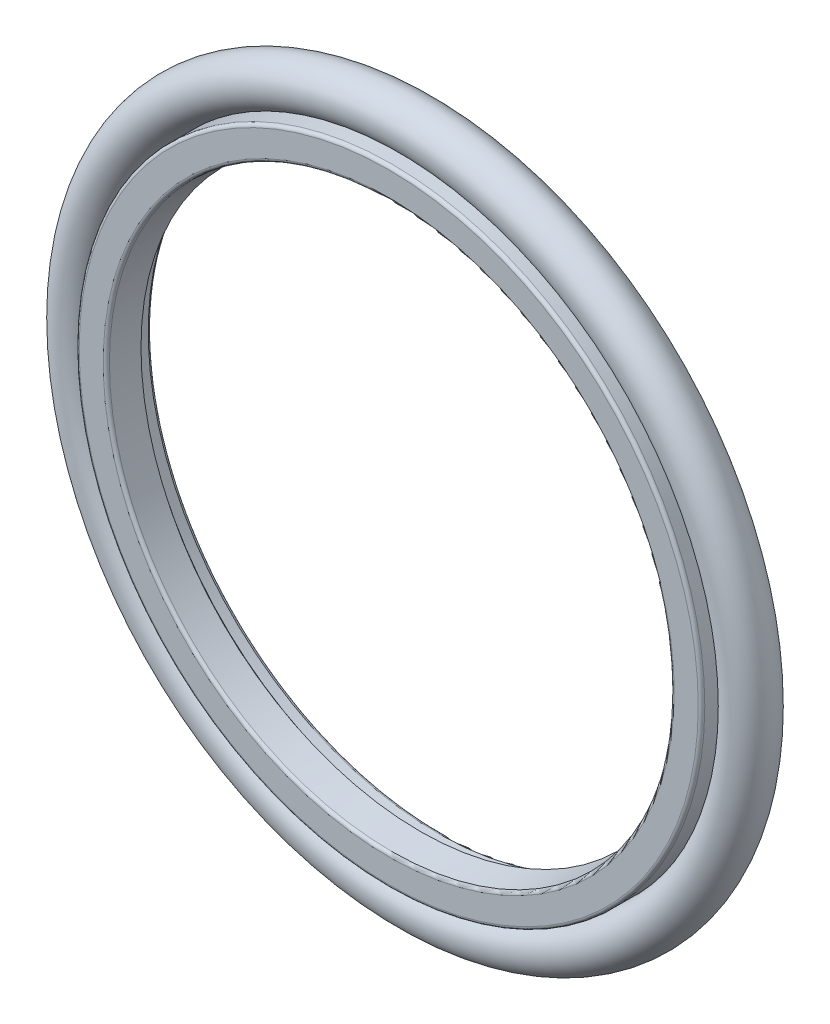
SolidWorks part; units mm, degrees
material "PTFE+NBR"
ref_plane "Front Plane" through (0, 0, 0) normal (0, 0, 1) x (1, 0, 0)
ref_plane "Top Plane" through (0, 0, 0) normal (0, 1, 0) x (1, 0, 0)
ref_plane "Right Plane" through (0, 0, 0) normal (1, 0, 0) x (0, 0, -1)
sketch "Sketch1" plane through (0, 0, 0) normal (1, 0, 0) x (0, 0, -1)
  line L0 (0, 0) -> (69.0954, 0) construction
  line L1 (0.25, 23.8) -> (3.75, 23.8)
  line L2 (0, 23.55) -> (0, 21.7253)
  line L3 (4, 23.55) -> (4, 22.3)
  line L4 (3.75, 22.05) -> (3, 22.05)
  line L5 (3, 22.05) -> (2.4, 21.25)
  line L6 (2.4, 21.25) -> (0.2241, 21.4767)
  arc A0 (0, 21.7253) -> (0.2241, 21.4767) centre (0.25, 21.7253) ccw
  arc A1 (4, 22.3) -> (3.75, 22.05) centre (3.75, 22.3) cw
  arc A2 (0.25, 23.8) -> (0, 23.55) centre (0.25, 23.55) ccw
  arc A3 (4, 23.55) -> (3.75, 23.8) centre (3.75, 23.55) ccw
  point P11 (0, 21.5)
  dimension "D8" = 0.25
  dimension "D1" = 1
  dimension "D2" = 1.6
  dimension "D3" = 4
  dimension "D4" = 43
  dimension "D5" = 47.6
  dimension "D6" = 42.5
  dimension "D7" = 44.1
revolve "Revolve1" add sketch "Sketch1" angle 360 about L0
sketch "Sketch2" plane through (0, 0, 0) normal (1, 0, 0) x (0, 0, -1)
  line L0 (2, 23.8) -> (2, 10.528) construction
  line L1 (3.75, 23.8) -> (0.25, 23.8) construction
  line L2 (0, 0) -> (10.3771, 0) construction
  circle A0 centre (2, 25.55) radius 1.75
  dimension "D1" = 3.5
revolve "Revolve2" add sketch "Sketch2" angle 360 about L2
